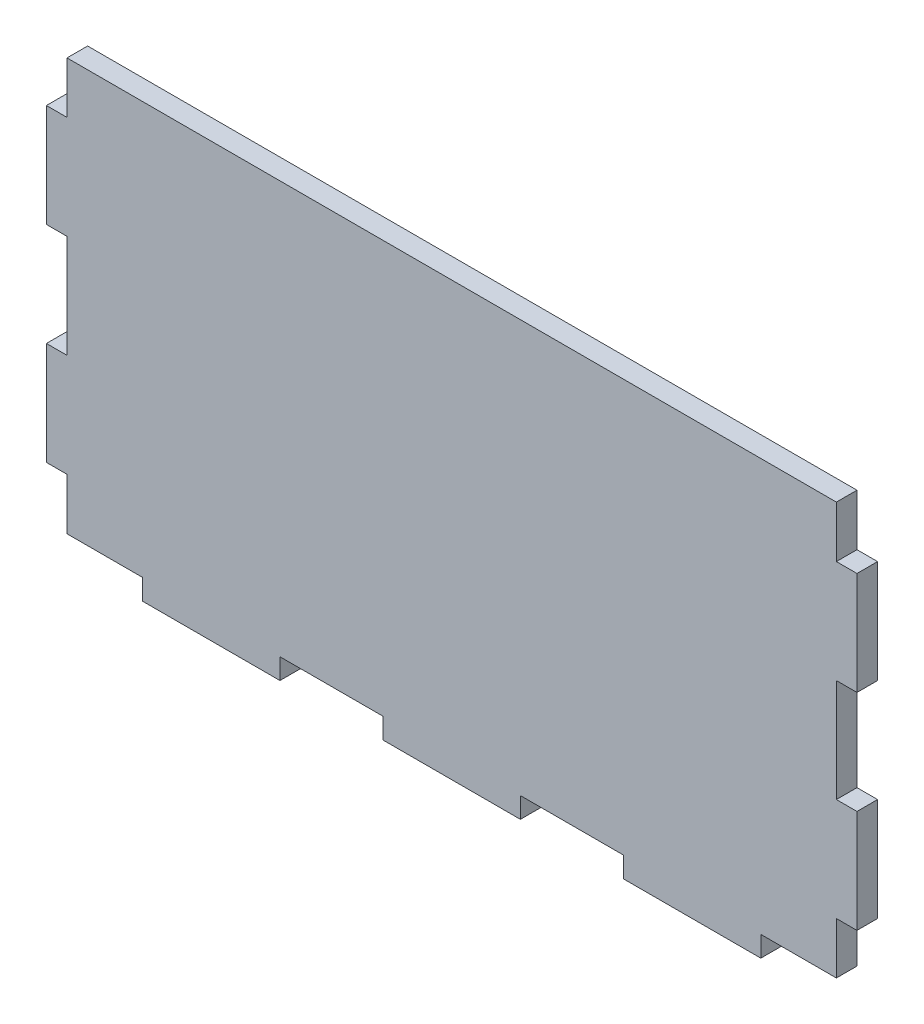
SolidWorks part; units mm, degrees
ref_plane "Front Plane" through (0, 0, 0) normal (0, 0, 1) x (1, 0, 0)
ref_plane "Top Plane" through (0, 0, 0) normal (0, 1, 0) x (1, 0, 0)
ref_plane "Right Plane" through (0, 0, 0) normal (1, 0, 0) x (0, 0, -1)
sketch "Sketch2" plane through (0, 0, 0) normal (0, 0, 1) x (1, 0, 0)
  line L0 (0, -55) -> (0, 55) construction
  line L1 (56, -30) -> (-56, -30)
  line L2 (56, -30) -> (56, 30)
  line L3 (56, 30) -> (-56, 30)
  line L4 (-56, -30) -> (-56, 30)
  line L5 (56, -30) -> (-56, 30) construction
  line L6 (56, 30) -> (-56, -30) construction
  line L7 (-10, -33) -> (10, -33)
  line L8 (-10, -33) -> (-10, -30)
  line L9 (-10, -30) -> (10, -30)
  line L10 (10, -33) -> (10, -30)
  line L11 (-10, -33) -> (10, -30) construction
  line L12 (-10, -30) -> (10, -33) construction
  line L13 (25, -33) -> (45, -33)
  line L14 (25, -33) -> (25, -30)
  line L15 (25, -30) -> (45, -30)
  line L16 (45, -33) -> (45, -30)
  line L17 (25, -33) -> (45, -30) construction
  line L18 (25, -30) -> (45, -33) construction
  line L19 (59, 7.5) -> (56, 7.5)
  line L20 (59, 7.5) -> (59, 22.5)
  line L21 (59, 22.5) -> (56, 22.5)
  line L22 (56, 7.5) -> (56, 22.5)
  line L23 (59, 7.5) -> (56, 22.5) construction
  line L24 (59, 22.5) -> (56, 7.5) construction
  line L25 (59, -22.5) -> (56, -22.5)
  line L26 (59, -22.5) -> (59, -7.5)
  line L27 (59, -7.5) -> (56, -7.5)
  line L28 (56, -22.5) -> (56, -7.5)
  line L29 (59, -22.5) -> (56, -7.5) construction
  line L30 (59, -7.5) -> (56, -22.5) construction
  line L31 (-59, 22.5) -> (-56, 22.5)
  line L32 (-56, 7.5) -> (-56, 22.5)
  line L33 (-59, 7.5) -> (-56, 7.5)
  line L34 (-59, 7.5) -> (-59, 22.5)
  line L35 (-59, -7.5) -> (-56, -7.5)
  line L36 (-56, -22.5) -> (-56, -7.5)
  line L37 (-59, -22.5) -> (-56, -22.5)
  line L38 (-59, -22.5) -> (-59, -7.5)
  line L39 (-25, -30) -> (-45, -30)
  line L40 (-45, -33) -> (-45, -30)
  line L41 (-25, -33) -> (-45, -33)
  line L42 (-25, -33) -> (-25, -30)
  line L43 (-10, -33) -> (-10, -30)
  line L44 (10, -33) -> (10, -30)
  point P0 (0, 0)
  point P6 (0, -31.5)
  point P11 (35, -31.5)
  point P16 (57.5, -15)
  point P17 (57.5, 15)
  dimension "D1" = 112
  dimension "D2" = 60
  dimension "D3" = 3
  dimension "D4" = 20
  dimension "D5" = 15
  dimension "D6" = 15
  dimension "D7" = 3
  dimension "D8" = 7.5
  dimension "D9" = 15
extrude "Boss-Extrude1" add sketch "Sketch2" along normal blind 3 contours L34 L33 L4 L31 | L38 L37 L4 L35 | L4 L1 L2 L3 | L41 L42 L1 L40 | L7 L10 L1 L8 | L13 L16 L1 L14 | L26 L27 L28 L25 | L20 L21 L22 L19
